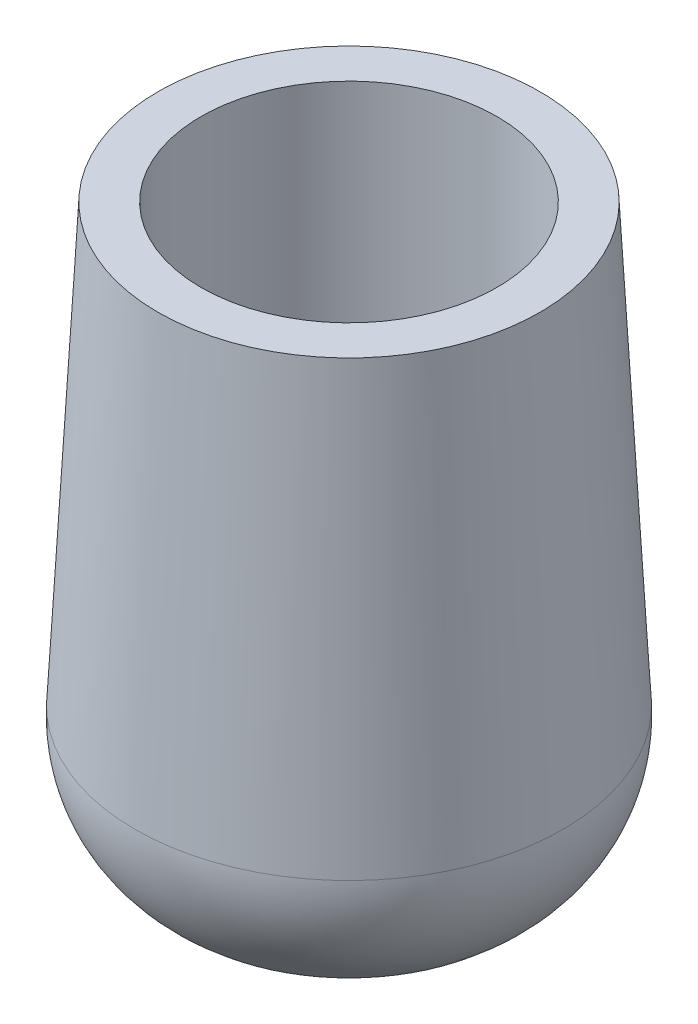
SolidWorks part; units mm, degrees
ref_plane "Plane1" through (0, 0, 0) normal (0, 0, 1) x (1, 0, 0)
ref_plane "Plane2" through (0, 0, 0) normal (0, 1, 0) x (1, 0, 0)
ref_plane "Plane3" through (0, 0, 0) normal (1, 0, 0) x (0, 0, -1)
sketch "Sketch2" plane through (0, 0, 0) normal (0, 1, 0) x (1, 0, 0)
  circle A0 centre (0, 0) radius 4.7625
  dimension "D1" = 9.525
extrude "Base-Extrude" add sketch "Sketch2" along normal blind 12.7 draft 3
fillet "Fillet1" radius 3.175 1 edges at (0, 0, 4.7625)
sketch "Sketch3" plane through (0, 12.7, 0) normal (0, 1, 0) x (-1, 0, 0)
  circle A0 centre (0, 0) radius 3.175
  circle A1 centre (0, 0) radius 4.0969 construction
  dimension "D1" = 6.35
extrude "Cut-Extrude1" cut sketch "Sketch3" against normal blind 6.35
